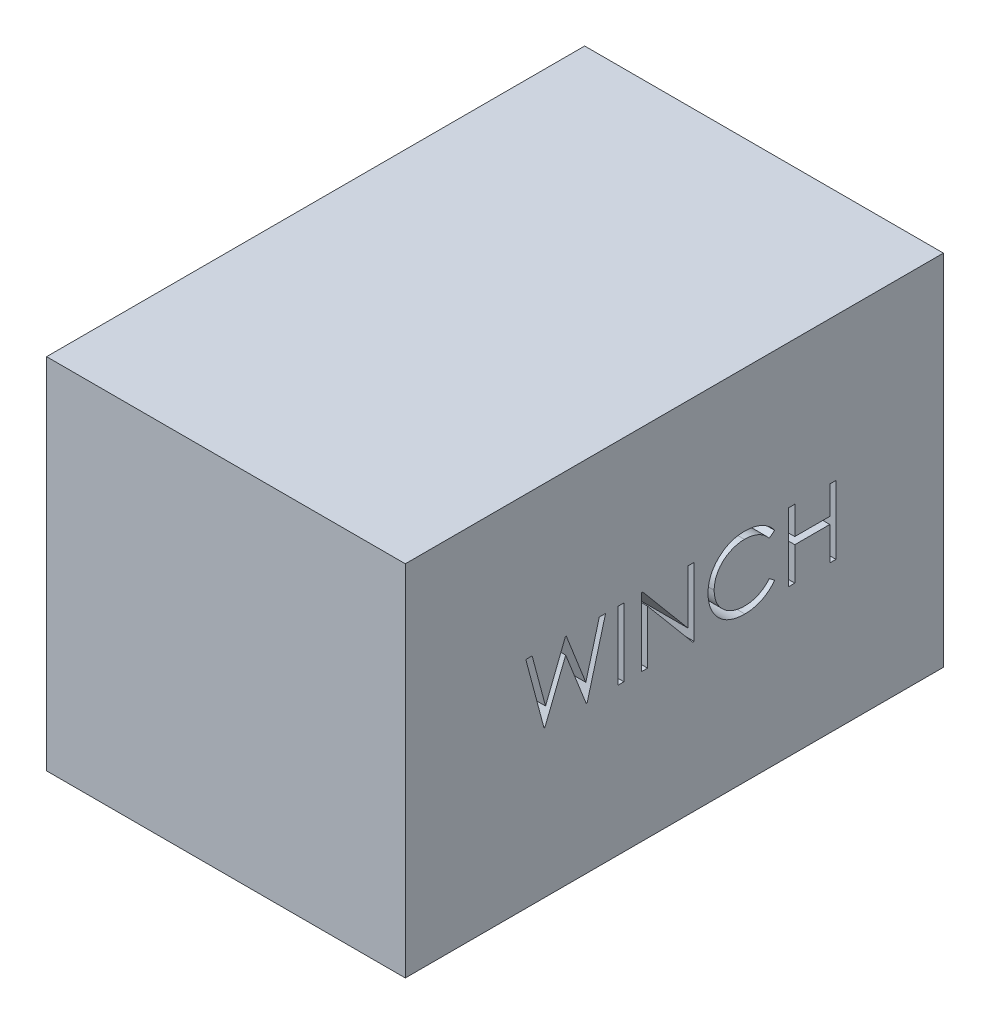
SolidWorks part; units mm, degrees
ref_plane "Front Plane" through (0, 0, 0) normal (0, 0, 1) x (1, 0, 0)
ref_plane "Top Plane" through (0, 0, 0) normal (0, 1, 0) x (1, 0, 0)
ref_plane "Right Plane" through (0, 0, 0) normal (1, 0, 0) x (0, 0, -1)
sketch "Sketch1" plane through (0, 0, 0) normal (0, 0, 1) x (1, 0, 0)
  line L1 (-55.5556, 57.8283) -> (44.4444, 57.8283)
  line L2 (-55.5556, 57.8283) -> (-55.5556, -42.1717)
  line L3 (-55.5556, -42.1717) -> (44.4444, -42.1717)
  line L4 (44.4444, 57.8283) -> (44.4444, -42.1717)
  dimension "D1" = 100
  dimension "D2" = 100
extrude "Boss-Extrude1" add sketch "Sketch1" along normal blind 150
sketch "Sketch2" plane through (44.4444, 0, 0) normal (1, 0, 0) x (0, 0, -1)
  text T0 "WINCH" font "Century Gothic" height in points 72
extrude "Cut-Extrude1" cut sketch "Sketch2" against normal blind 30
